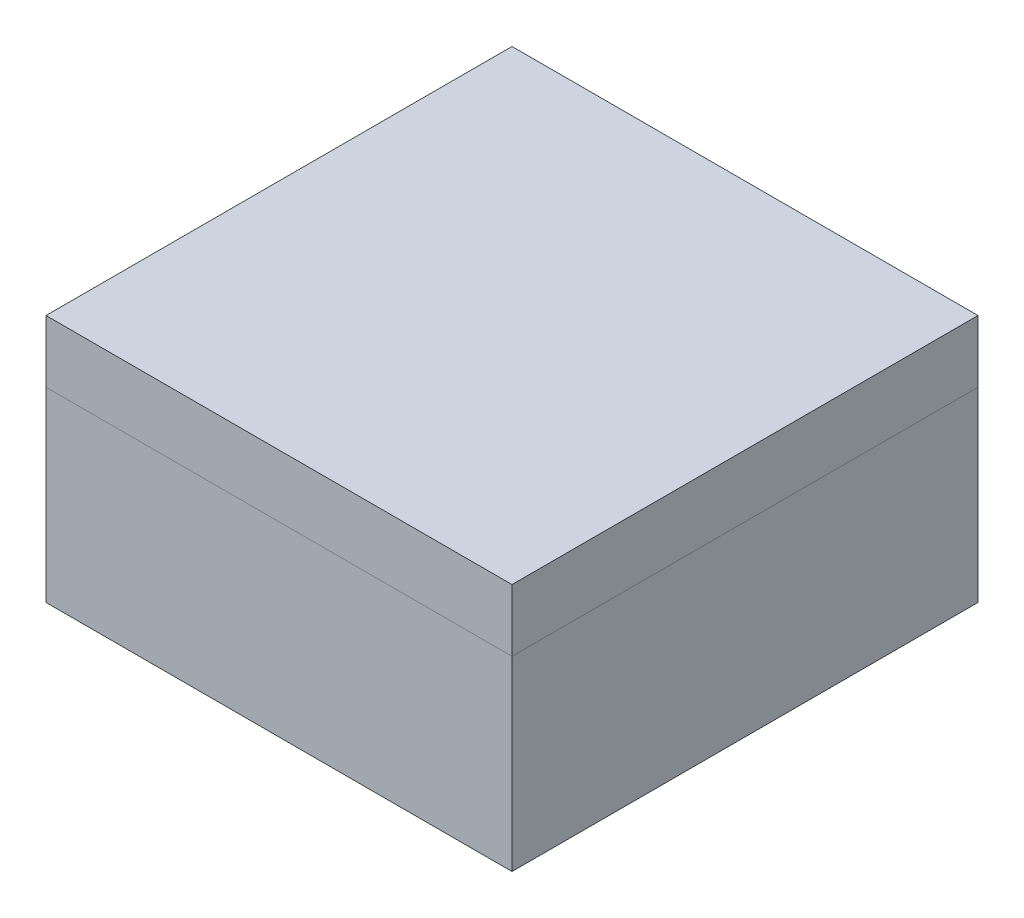
SolidWorks part; units mm, degrees
ref_plane "前视基准面" through (0, 0, 0) normal (0, 0, 1) x (1, 0, 0)
ref_plane "上视基准面" through (0, 0, 0) normal (0, 1, 0) x (1, 0, 0)
ref_plane "右视基准面" through (0, 0, 0) normal (1, 0, 0) x (0, 0, -1)
sketch "草图1" plane through (0, 0, 0) normal (0, 1, 0) x (1, 0, 0)
  line L1 (-7.5, -7.5) -> (7.5, -7.5)
  line L2 (-7.5, -7.5) -> (-7.5, 7.5)
  line L3 (-7.5, 7.5) -> (7.5, 7.5)
  line L4 (7.5, -7.5) -> (7.5, 7.5)
  line L5 (-7.5, -7.5) -> (7.5, 7.5) construction
  line L6 (-7.5, 7.5) -> (7.5, -7.5) construction
  point P0 (0, 0)
  dimension "D1" = 15
  dimension "D2" = 15
extrude "凸台-拉伸1" add sketch "草图1" along normal blind 5
sketch "草图2" plane through (0, 5, 0) normal (0, 1, 0) x (1, 0, 0)
  circle A0 centre (0, 0) radius 4.1
  dimension "D1" = 8.2
extrude "切除-拉伸1" cut sketch "草图2" against normal blind 6
sketch "草图3" plane through (0, 5, 0) normal (0, 1, 0) x (1, 0, 0)
  line L4 (7.5, -7.5) -> (7.5, 7.5)
  line L5 (7.5, 7.5) -> (-7.5, 7.5)
  line L6 (-7.5, 7.5) -> (-7.5, -7.5)
  line L7 (-7.5, -7.5) -> (7.5, -7.5)
  line L8 (7.5, -7.5) -> (7.5, 7.5)
  line L9 (7.5, 7.5) -> (-7.5, 7.5)
  line L10 (-7.5, 7.5) -> (-7.5, -7.5)
  line L11 (-7.5, -7.5) -> (7.5, -7.5)
  dimension "D1" = 0
extrude "凸台-拉伸2" add sketch "草图3" along normal blind 1
sketch "草图4" plane through (0, 6, 0) normal (0, 1, 0) x (1, 0, 0)
  line L4 (-7.5, -7.5) -> (7.5, -7.5)
  line L5 (7.5, -7.5) -> (7.5, 7.5)
  line L6 (7.5, 7.5) -> (-7.5, 7.5)
  line L7 (-7.5, 7.5) -> (-7.5, -7.5)
  line L8 (-7.5, -7.5) -> (7.5, -7.5)
  line L9 (7.5, -7.5) -> (7.5, 7.5)
  line L10 (7.5, 7.5) -> (-7.5, 7.5)
  line L11 (-7.5, 7.5) -> (-7.5, -7.5)
  dimension "D1" = 0
extrude "凸台-拉伸3" add sketch "草图4" along normal blind 2 separate body
